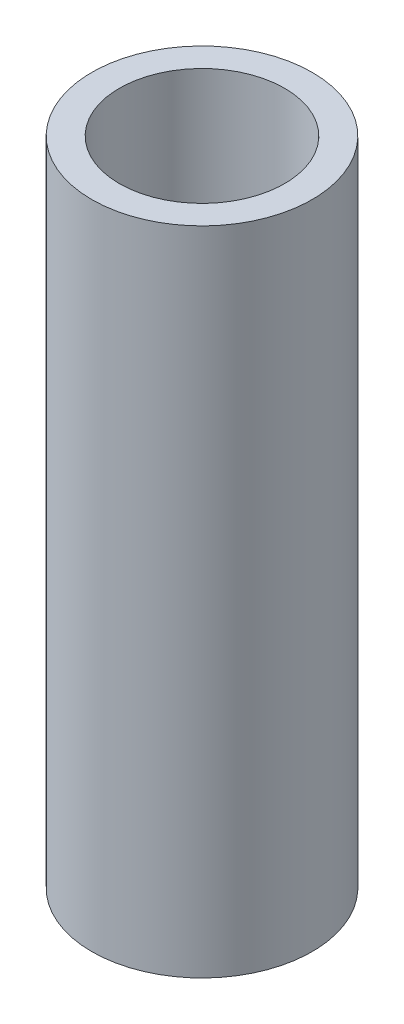
SolidWorks part; units mm, degrees
ref_plane "Front Plane" through (0, 0, 0) normal (0, 0, 1) x (1, 0, 0)
ref_plane "Top Plane" through (0, 0, 0) normal (0, 1, 0) x (1, 0, 0)
ref_plane "Right Plane" through (0, 0, 0) normal (1, 0, 0) x (0, 0, -1)
sketch "Sketch1" plane through (0, 0, 0) normal (0, 0, 1) x (1, 0, 0)
  line L0 (0, 0) -> (0, -59.1089)
sweep "Sweep1" add path "Sketch1" circular profile diameter 20 parameters "D3"=20
sketch "Sketch3" plane through (0, 0, 0) normal (0, 1, 0) x (1, 0, 0)
  circle A0 centre (0, 0) radius 7.5
  dimension "D1" = 15
extrude "Cut-Extrude2" cut sketch "Sketch3" against normal blind 70
